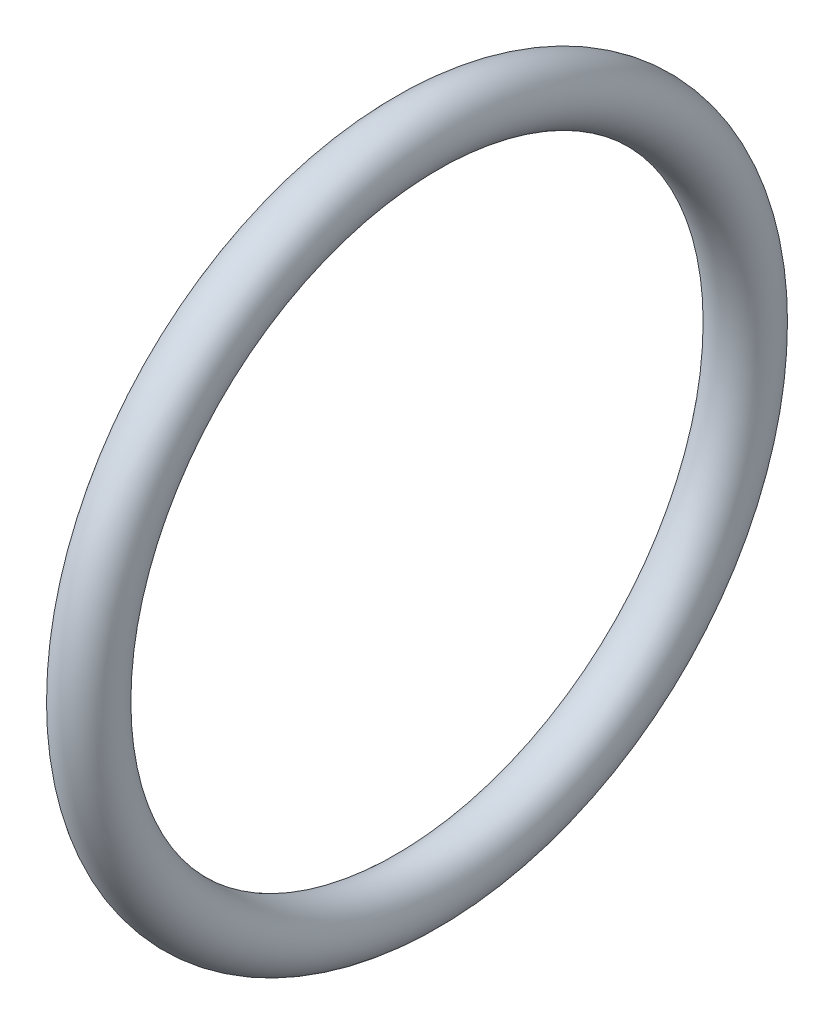
SolidWorks part; units mm, degrees
ref_plane "前视基准面" through (0, 0, 0) normal (0, 0, 1) x (1, 0, 0)
ref_plane "上视基准面" through (0, 0, 0) normal (0, 1, 0) x (1, 0, 0)
ref_plane "右视基准面" through (0, 0, 0) normal (1, 0, 0) x (0, 0, -1)
other "Configuration Table"
sketch "草图1" plane through (0, 0, 0) normal (0, 0, 1) x (1, 0, 0)
  line L0 (-20.884, 0) -> (20.2255, 0) construction
  line L1 (0, 27.2168) -> (0, -25.2755) construction
  circle A0 centre (0, 27.5) radius 2.5
  dimension "D1" = 5
  dimension "D2" = 27.5
revolve "旋转1" add sketch "草图1" angle 360 about L0
sketch "草图2" plane through (0, 0, 0) normal (1, 0, 0) x (0, 0, -1)
  circle A0 centre (0, 0) radius 27.5 construction
  dimension "D1" = 55
